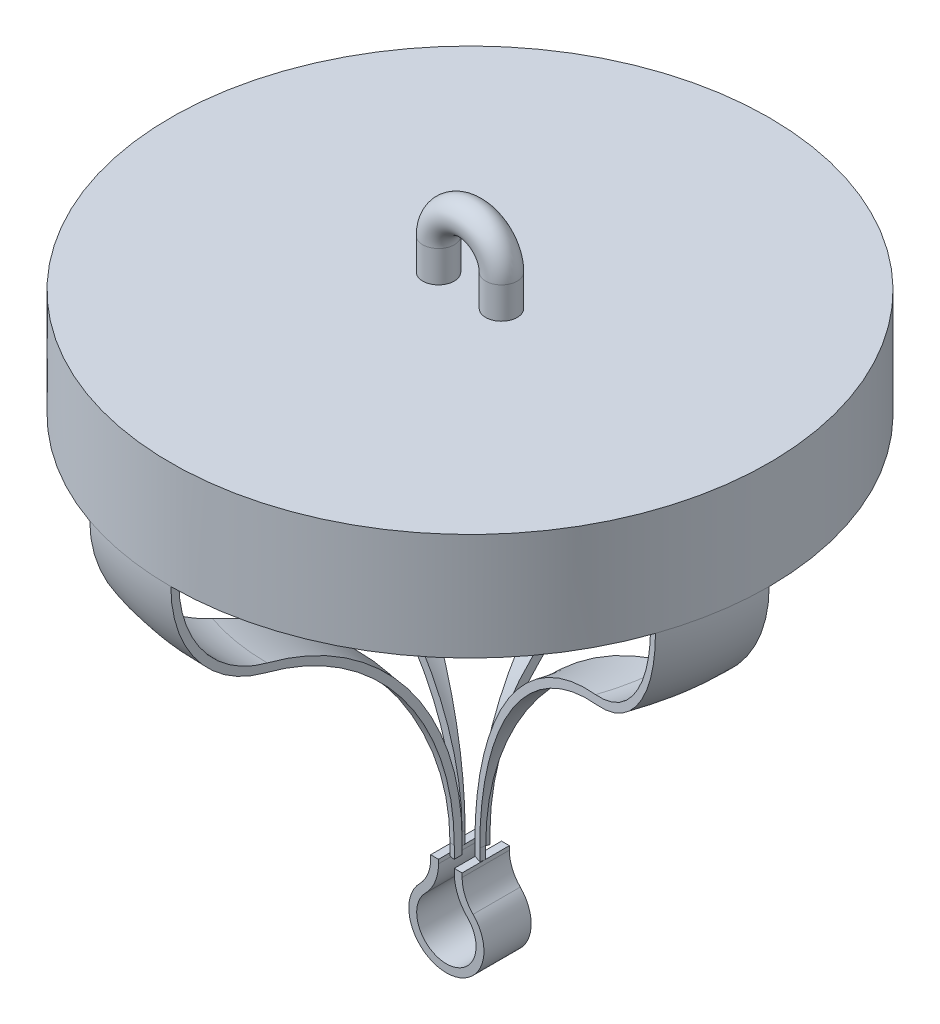
SolidWorks part; units mm, degrees
ref_plane "Front Plane" through (0, 0, 0) normal (0, 0, 1) x (1, 0, 0)
ref_plane "Top Plane" through (0, 0, 0) normal (0, 1, 0) x (1, 0, 0)
ref_plane "Right Plane" through (0, 0, 0) normal (1, 0, 0) x (0, 0, -1)
sketch "Sketch1" plane through (0, 0, 0) normal (0, 0, 1) x (1, 0, 0)
  line L0 (0, 0) -> (0, 33.6698) construction
  line L1 (0, 0) -> (60.325, 0)
  line L2 (60.325, 0) -> (60.325, 21.59)
  line L3 (60.325, 21.59) -> (0, 21.59)
  line L4 (0, 21.59) -> (0, 0)
  dimension "D1" = 120.65
  dimension "D2" = 21.59
revolve "Revolve1" add sketch "Sketch1" angle 360 about L0
sketch "Sketch3" plane through (0, 21.59, 0) normal (0, 1, 0) x (1, 0, 0)
  circle A0 centre (0, 0) radius 1.5875
  dimension "D1" = 3.175
sketch "Sketch4" plane through (0, 0, 0) normal (0, 0, 1) x (1, 0, 0)
  line L0 (60.325, 0) -> (60.325, 6.35)
  line L1 (60.325, 0) -> (60.325, 21.59) construction
  line L2 (0, 0) -> (0, -57.5314) construction
  line L3 (-60.325, 0) -> (60.325, 0) construction
  line L4 (3.175, -73.7803) -> (3.175, -76.2)
  line L5 (1.5875, -73.7803) -> (1.5875, -76.2)
  line L6 (58.7375, 0) -> (58.7375, 6.35)
  line L7 (1.5875, -76.2) -> (3.175, -76.2)
  line L8 (58.7375, 6.35) -> (60.325, 6.35)
  arc A0 (60.325, 0) -> (41.275, -24.5934) centre (34.925, 0) cw
  arc A1 (41.275, -24.5934) -> (3.175, -73.7803) centre (53.975, -73.7803) ccw
  arc A2 (40.8781, -23.0564) -> (1.5875, -73.7803) centre (53.975, -73.7803) ccw
  arc A3 (58.7375, 0) -> (40.8781, -23.0564) centre (34.925, 0) cw
  dimension "D2" = 25.4
  dimension "D3" = 50.8
  dimension "D1" = 6.35
  dimension "D4" = 76.2
  dimension "D5" = 6.35
  dimension "D6" = 1.5875
revolve "Revolve2" add sketch "Sketch4" angle 19 about L2
pattern_circular "CirPattern2" count 4 over 360 of "Revolve2"
sketch "Sketch5" plane through (0, -76.2, 0) normal (0, -1, 0) x (1, 0, 0)
  line L0 (-9.525, 1.5875) -> (9.525, 1.5875)
  line L1 (-9.525, 1.5875) -> (-9.525, -1.5875)
  line L2 (9.525, 1.5875) -> (9.525, -1.5875)
  line L3 (-9.525, -1.5875) -> (9.525, -1.5875)
  line L4 (-9.525, 0) -> (9.525, 0) construction
  dimension "D1" = 3.175
  dimension "D2" = 19.05
sketch "Sketch6" plane through (0, 0, 0) normal (0, 0, 1) x (1, 0, 0)
  line L0 (3.175, -76.2) -> (3.175, -76.9938)
  line L1 (-3.175, -76.9938) -> (-3.175, -76.2)
  line L2 (1.501, -76.2) -> (3.002, -76.2) construction
  line L3 (1.5875, -76.2) -> (1.5875, -76.9938)
  line L4 (-1.5875, -76.9938) -> (-1.5875, -76.2)
  line L5 (-3.175, -76.2) -> (-1.5875, -76.2)
  line L6 (1.5875, -76.2) -> (3.175, -76.2)
  arc A0 (3.175, -76.9938) -> (5.3761, -82.3333) centre (10.7521, -76.9938) ccw
  arc A1 (5.3761, -82.3333) -> (-5.3761, -82.3333) centre (0, -87.6729) cw
  arc A2 (-5.3761, -82.3333) -> (-3.175, -76.9938) centre (-10.7521, -76.9938) ccw
  arc A3 (1.5875, -76.9938) -> (4.2497, -83.452) centre (10.7521, -76.9938) ccw
  arc A4 (4.2497, -83.452) -> (-4.2497, -83.452) centre (0, -87.6729) cw
  arc A5 (-4.2497, -83.452) -> (-1.5875, -76.9938) centre (-10.7521, -76.9938) ccw
  point P12 (0, -95.25)
  dimension "D1" = 0.7937
  dimension "D2" = 19.05
  dimension "D3" = 1.5875
extrude "Boss-Extrude1" add sketch "Sketch6" along normal mid plane 9.525
sketch "Sketch7" plane through (0, 0, 0) normal (0, 0, 1) x (1, 0, 0)
  line L0 (6.35, 21.59) -> (6.35, 27.94)
  line L1 (60.325, 21.59) -> (-60.325, 21.59) construction
  line L2 (-6.35, 27.94) -> (-6.35, 21.59)
  arc A0 (6.35, 27.94) -> (-6.35, 27.94) centre (0, 27.94) ccw
  point P6 (0, 0)
  dimension "D1" = 6.35
  dimension "D2" = 6.35
sketch "Sketch8" plane through (0, 21.59, 0) normal (0, 1, 0) x (1, 0, 0)
  circle A0 centre (6.35, 0) radius 3.175
  dimension "D1" = 6.35
sweep "Sweep1" add profiles "Sketch8" path "Sketch7"
